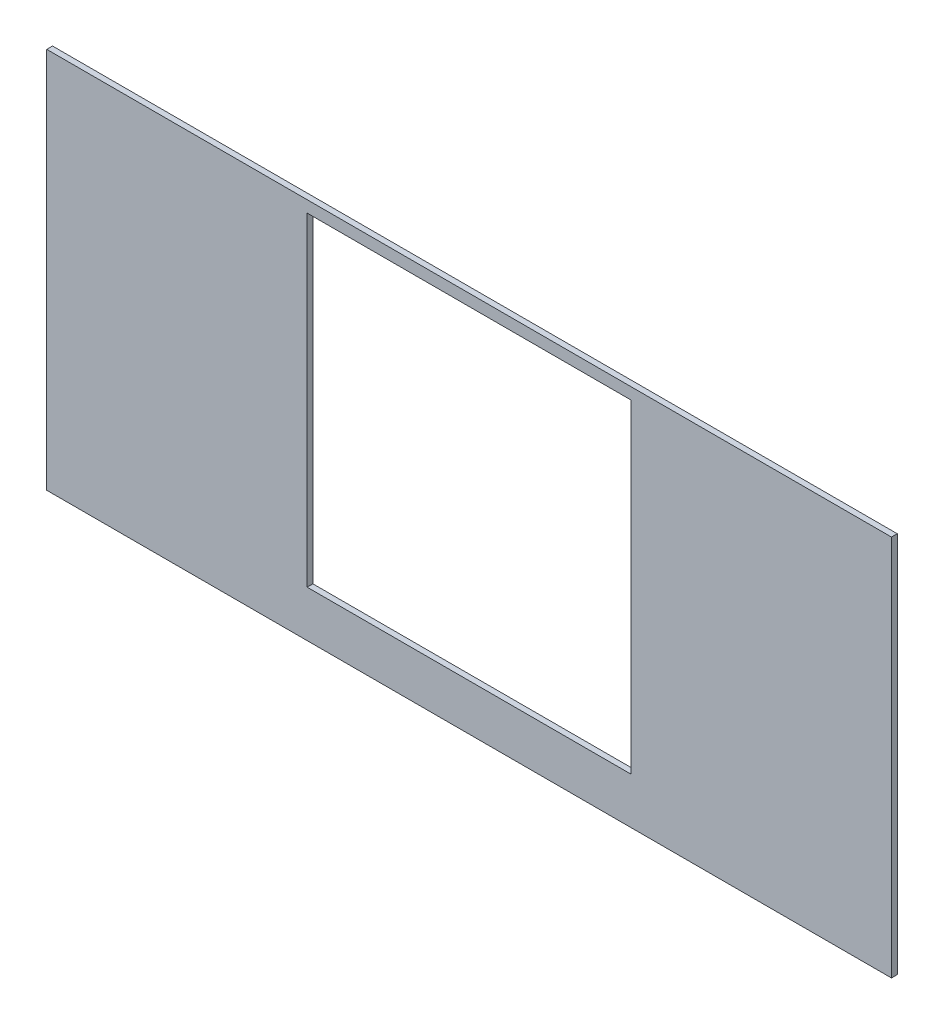
SolidWorks part; units mm, degrees
ref_plane "Alzado" through (0, 0, 0) normal (0, 0, 1) x (1, 0, 0)
ref_plane "Planta" through (0, 0, 0) normal (0, 1, 0) x (1, 0, 0)
ref_plane "Vista lateral" through (0, 0, 0) normal (1, 0, 0) x (0, 0, -1)
sketch "Croquis2" plane through (0, 0, 0) normal (0, 0, 1) x (1, 0, 0)
  line L1 (-365, -165) -> (365, -165)
  line L2 (-365, -165) -> (-365, 165)
  line L3 (-365, 165) -> (365, 165)
  line L4 (365, -165) -> (365, 165)
  line L5 (-365, -165) -> (365, 165) construction
  line L6 (-365, 165) -> (365, -165) construction
  point P0 (0, 0)
  dimension "D1" = 730
  dimension "D2" = 330
extrude "Saliente-Extruir2" add sketch "Croquis2" along normal blind 5
sketch "Croquis4" plane through (0, 0, 5) normal (0, 0, 1) x (1, 0, 0)
  line L0 (365, 165) -> (-365, 165) construction
  line L1 (140, 155) -> (-140, 155)
  line L2 (140, 155) -> (140, -125)
  line L3 (140, -125) -> (-140, -125)
  line L4 (-140, 155) -> (-140, -125)
  line L5 (365, -165) -> (365, 165) construction
  line L6 (-365, 165) -> (-365, -165) construction
  line L7 (-365, -165) -> (365, -165) construction
  dimension "D1" = 10
  dimension "D2" = 225
  dimension "D3" = 225
  dimension "D4" = 40
extrude "Cortar-Extruir1" cut sketch "Croquis4" against normal up to surface (5 mm away) up to face at (0, 0, 0)
